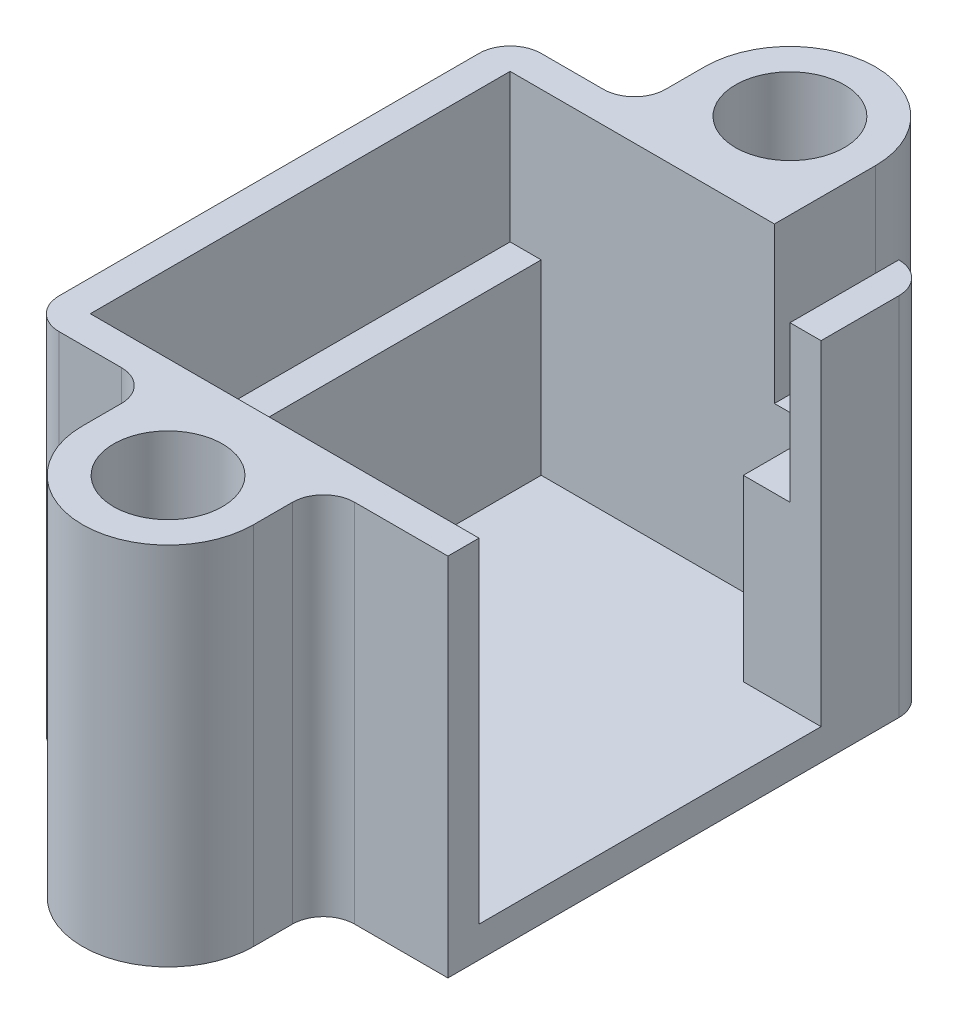
SolidWorks part; units mm, degrees
ref_plane "Front Plane" through (0, 0, 0) normal (0, 0, 1) x (1, 0, 0)
ref_plane "Top Plane" through (0, 0, 0) normal (0, 1, 0) x (1, 0, 0)
ref_plane "Right Plane" through (0, 0, 0) normal (1, 0, 0) x (0, 0, -1)
sketch "Sketch1" plane through (0, 0, 0) normal (0, 1, 0) x (1, 0, 0)
  line L1 (-5.75, 6.75) -> (5.75, 6.75)
  line L2 (-5.75, 6.75) -> (-5.75, -6.75)
  line L3 (-5.75, -6.75) -> (5.75, -6.75)
  line L4 (5.75, 6.75) -> (5.75, -6.75)
  line L5 (-5.75, 6.75) -> (5.75, -6.75) construction
  line L6 (-5.75, -6.75) -> (5.75, 6.75) construction
  line L7 (-6.75, 7.75) -> (6.75, 7.75)
  line L8 (-6.75, 7.75) -> (-6.75, -7.75)
  line L9 (-6.75, -7.75) -> (6.75, -7.75)
  line L10 (6.75, 7.75) -> (6.75, -7.75)
  line L11 (-6.75, 7.75) -> (6.75, -7.75) construction
  line L12 (-6.75, -7.75) -> (6.75, 7.75) construction
  point P0 (0, 0)
  point P6 (0, 0)
  dimension "D1" = 13.5
  dimension "D2" = 11.5
  dimension "D3" = 1
  dimension "D4" = 1
extrude "Boss-Extrude1" add sketch "Sketch1" along normal blind 1 contours L4 L1 L2 L3 | L10 L7 L8 L9 L1 L4 L3 L2
sketch "Sketch2" plane through (0, 1, 0) normal (0, 1, 0) x (1, 0, 0)
  line L8 (6.75, -7.75) -> (6.75, 7.75)
  line L9 (6.75, 7.75) -> (-6.75, 7.75)
  line L10 (-6.75, 7.75) -> (-6.75, -7.75)
  line L11 (-6.75, -7.75) -> (6.75, -7.75)
  line L12 (6.75, -7.75) -> (6.75, 7.75)
  line L13 (6.75, 7.75) -> (-6.75, 7.75)
  line L14 (-6.75, 7.75) -> (-6.75, -7.75)
  line L15 (-6.75, -7.75) -> (6.75, -7.75)
  line L17 (5.75, -6.75) -> (6.75, -6.75)
  line L18 (5.75, -6.75) -> (5.75, 4.25)
  line L19 (5.75, 4.25) -> (6.75, 4.25)
  line L20 (5.75, -6.75) -> (5.75, 6.75)
  line L21 (5.75, 6.75) -> (-5.75, 6.75)
  line L22 (-5.75, 6.75) -> (-5.75, -6.75)
  line L23 (-5.75, -6.75) -> (5.75, -6.75)
  line L24 (5.75, -6.75) -> (5.75, 6.75)
  line L25 (5.75, 6.75) -> (-5.75, 6.75)
  line L26 (-5.75, 6.75) -> (-5.75, -6.75)
  line L27 (-5.75, -6.75) -> (5.75, -6.75)
  line L28 (6.75, -6.75) -> (6.75, 4.25)
  dimension "D3" = 11
  dimension "D1" = 0
  dimension "D2" = 1
extrude "Boss-Extrude2" add sketch "Sketch2" along normal blind 10.75
sketch "Sketch3" plane through (0, 11.75, 0) normal (0, 1, 0) x (1, 0, 0)
  line L0 (6.75, 7.75) -> (-6.75, 7.75) construction
  line L3 (5.75, 6.75) -> (2.75, 6.75)
  line L4 (5.75, 6.75) -> (5.75, 7.75)
  line L7 (5.75, 7.75) -> (2.75, 7.75)
  line L8 (2.75, 6.75) -> (2.75, 7.75)
  dimension "D1" = 3
extrude "Cut-Extrude1" cut sketch "Sketch3" against normal blind 5
sketch "Sketch4" plane through (0, 11.75, 0) normal (0, 1, 0) x (1, 0, 0)
  line L0 (0, 4.7306) -> (0, -2.1192) construction
  line L1 (-6.75, 0) -> (6.75, 0) construction
  line L2 (-6.75, 7.75) -> (-6.75, -7.75) construction
  line L3 (6.75, 4.25) -> (6.75, -6.75) construction
  line L4 (-2.75, 10) -> (-2.75, 7.75)
  line L5 (2.75, 7.75) -> (-6.75, 7.75) construction
  line L6 (2.75, 10) -> (2.75, 7.75)
  line L7 (5.75, 7.75) -> (2.75, 7.75) construction
  line L8 (-2.75, -10) -> (-2.75, -7.75)
  line L9 (2.75, -10) -> (2.75, -7.75)
  line L10 (-2.75, 7.75) -> (2.75, 7.75)
  line L11 (-2.75, -7.75) -> (2.75, -7.75)
  circle A0 centre (0, 10) radius 1.75
  circle A1 centre (0, 10) radius 2.75
  circle A2 centre (0, -10) radius 1.75
  circle A3 centre (0, -10) radius 2.75
  line M2 (2.75, 7.75) -> (-6.75, 7.75)
  line M4 (-6.75, -7.75) -> (6.75, -7.75)
  dimension "D1" = 3.5
  dimension "D3" = 1
  dimension "D2" = 20
extrude "Boss-Extrude3" add sketch "Sketch4" against normal up to surface (11.75 mm away) contours L10 A1 A0 | A1 L4 M2 | A1 L10 L6 M2 | L8 A3 M4 | A3 L11 A2 | A3 L9 M4 up to face at (0, 0, 0)
fillet "Fillet1" radius 1 19 edges at (6.25, 11.75, -7.75) (-6.75, 5.875, 7.75) (-6.75, 5.875, -7.75) (6.75, 5.875, -7.75)
sketch "Sketch5" plane through (0, 1, 0) normal (0, 1, 0) x (1, 0, 0)
  line L1 (-5.75, 6.75) -> (-4.75, 6.75)
  line L2 (-5.75, 6.75) -> (-5.75, -6.75)
  line L3 (-5.75, -6.75) -> (-4.75, -6.75)
  line L4 (-4.75, 6.75) -> (-4.75, -6.75)
  dimension "D1" = 1
extrude "Boss-Extrude4" add sketch "Sketch5" along normal blind 6
sketch "Sketch6" plane through (0, 1, 0) normal (0, 1, 0) x (1, 0, 0)
  line L0 (5.75, 4.25) -> (6.75, 4.25) construction
  line L1 (5.75, 6.75) -> (4.25, 6.75)
  line L2 (5.75, 6.75) -> (5.75, 4.25)
  line L3 (5.75, 4.25) -> (4.25, 4.25)
  line L4 (4.25, 6.75) -> (4.25, 4.25)
  dimension "D1" = 1.5
extrude "Boss-Extrude5" add sketch "Sketch6" along normal up to surface (5.75 mm away) up to face at (4.3086, 6.75, -7.7086)
